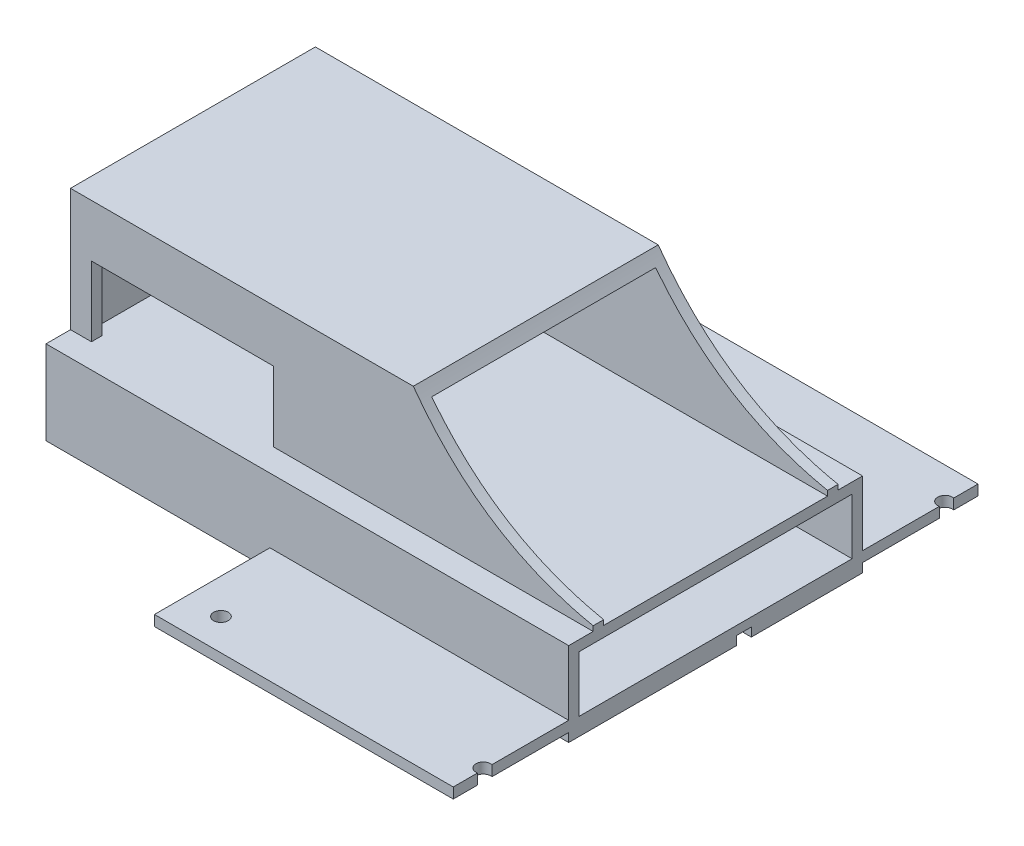
SolidWorks part; units mm, degrees
ref_plane "Plan de face" through (0, 0, 0) normal (0, 0, 1) x (1, 0, 0)
ref_plane "Plan de dessus" through (0, 0, 0) normal (0, 1, 0) x (1, 0, 0)
ref_plane "Plan de droite" through (0, 0, 0) normal (1, 0, 0) x (0, 0, -1)
sketch "Esquisse1" plane through (0, 0, 0) normal (0, 1, 0) x (1, 0, 0)
  line L0 (-54.2982, 57.973) -> (101.7018, 57.973)
  line L1 (-54.2982, 57.973) -> (-54.2982, -26.027)
  line L2 (101.7018, 57.973) -> (101.7018, -26.027)
  line L3 (-54.2982, -26.027) -> (101.7018, -26.027)
  dimension "D1" = 156
  dimension "D2" = 84
extrude "Boss.-Extru.1" add sketch "Esquisse1" along normal blind 59
sketch "Esquisse2" plane through (101.7018, 0, 0) normal (1, 0, 0) x (0, 0, -1)
  line L0 (57.973, 0) -> (57.973, 5)
  line L1 (57.973, 59) -> (57.973, 0) construction
  line L2 (57.973, 5) -> (-26.027, 5)
  line L3 (-26.027, 59) -> (-26.027, 0) construction
  line L4 (-26.027, 5) -> (-26.027, 0)
  line L6 (15.973, 0) -> (21.973, 0)
  line L7 (21.973, 0) -> (21.973, 2.5)
  line L8 (21.973, 2.5) -> (26.173, 2.5)
  line L9 (26.173, 2.5) -> (26.173, 0)
  line L11 (-26.027, 5) -> (-23.027, 5)
  line L12 (-23.027, 5) -> (-23.027, 21)
  line L13 (-23.027, 21) -> (54.973, 21)
  line L14 (54.973, 21) -> (54.973, 5)
  line L15 (54.973, 21) -> (54.973, 24)
  line L16 (54.973, 24) -> (-26.027, 24)
  line L17 (-26.027, 24) -> (57.973, 24)
  line L18 (15.973, 24) -> (47.973, 24)
  line L19 (47.973, 24) -> (47.973, 56)
  line L20 (47.973, 56) -> (-16.027, 56)
  line L21 (-16.027, 56) -> (-16.027, 24)
  line L22 (-16.027, 24) -> (47.973, 24)
  line L23 (47.973, 24) -> (50.973, 24)
  line L24 (50.973, 24) -> (50.973, 59)
  line L25 (-26.027, 59) -> (57.973, 59) construction
  line L26 (-16.027, 24) -> (-19.027, 24)
  line L27 (-19.027, 24) -> (-19.027, 59)
  line L28 (-19.027, 59) -> (50.973, 59)
  line L29 (57.973, 59) -> (57.973, 24)
  line L30 (50.973, 59) -> (57.973, 59)
  line L31 (-19.027, 59) -> (-26.027, 59)
  line L32 (-26.027, 59) -> (-26.027, 24)
  line L33 (21.973, 0) -> (26.173, 0)
  line M8 (-26.027, 0) -> (57.973, 0)
  line M9 (57.973, 0) -> (57.973, 59)
  line M10 (57.973, 59) -> (-26.027, 59)
  line M11 (-26.027, 59) -> (-26.027, 0)
  dimension "D1" = 84
extrude "Enlèv. mat.-Extru.1" cut sketch "Esquisse2" against normal through all contours L20 L21 L16 L17 L19 | L14 L13 L12 L2 | L16 L27 M10 M11 | L24 L16 L17 M9 M10 | L9 L8 L7 M8
sketch "Esquisse3" plane through (0, 0, 19.027) normal (0, 0, 1) x (1, 0, 0)
  line L0 (-54.2982, 59) -> (40.7018, 59)
  line L1 (-54.2982, 59) -> (101.7018, 59) construction
  line L2 (40.7018, 59) -> (40.7018, 24)
  line L3 (-54.2982, 24) -> (101.7018, 24) construction
  line L4 (40.7018, 24) -> (-54.2982, 24)
  line L5 (-54.2982, 24) -> (-54.2982, 59) construction
  line L6 (-54.2982, 24) -> (-54.2982, 59)
  line L7 (40.7018, 59) -> (101.7018, 59)
  line L8 (101.7018, 59) -> (101.7018, 24)
  line L9 (101.7018, 24) -> (40.7018, 24)
  spline S0 degree 2 poles (40.7018, 59) (63.2327, 27.7967) (101.7018, 24) knots 0 0 0 1 1 1
  line M1 (101.7018, 24) -> (101.7018, 59)
  line M2 (101.7018, 59) -> (-54.2982, 59)
extrude "Enlèv. mat.-Extru.3" cut sketch "Esquisse3" against normal through all contours S0 M2 M1
sketch "Esquisse4" plane through (0, 0, 19.027) normal (0, 0, 1) x (1, 0, 0)
  line L0 (-54.2982, 24) -> (-51.2982, 24)
  line L1 (-54.2982, 24) -> (101.7018, 24) construction
  line L2 (-51.2982, 24) -> (-51.2982, 44)
  line L3 (-51.2982, 44) -> (0.7018, 44)
  line L4 (0.7018, 44) -> (0.7018, 24)
  line L5 (0.7018, 24) -> (-51.2982, 24)
  line M1 (-54.2982, 24) -> (101.7018, 24)
extrude "Enlèv. mat.-Extru.4" cut sketch "Esquisse4" against normal blind 59 contours L4 L3 L2 M1
sketch "Esquisse5" plane through (0, 0, -57.973) normal (0, 0, -1) x (-1, 0, 0)
  line L0 (54.2982, 0) -> (54.2982, 2.5)
  line L1 (54.2982, 24) -> (54.2982, 0) construction
  line L2 (54.2982, 2.5) -> (54.2982, 5.5)
  line L3 (54.2982, 0) -> (-40.7018, 0)
  line L4 (-101.7018, 0) -> (54.2982, 0) construction
  line L5 (-40.7018, 0) -> (-40.7018, 5.5)
  line L7 (54.2982, 2.5) -> (-40.7018, 2.75)
  line L9 (-101.7018, 24) -> (-101.7018, 0) construction
  line L10 (-101.7018, 5.5) -> (-101.7018, 2.5)
  line L11 (-101.7018, 2.5) -> (-40.7018, 2.75)
  line L12 (-101.7018, 5.5) -> (-6.7018, 5.5)
  line L13 (-6.7018, 5.5) -> (-6.7018, 2.6605)
  line M7 (-101.7018, 24) -> (-101.7018, 0)
extrude "Boss.-Extru.2" add sketch "Esquisse5" along normal blind 34 contours L12 L11 L5 M7 | L13 L12 L5 L7
sketch "Esquisse6" plane through (0, 0, 26.027) normal (0, 0, 1) x (1, 0, 0)
  line L0 (-54.2982, 0) -> (-54.2982, 2.5)
  line L1 (-54.2982, 24) -> (-54.2982, 0) construction
  line L2 (-54.2982, 2.5) -> (-54.2982, 5.5)
  line L6 (101.7018, 0) -> (101.7018, 2.5)
  line L7 (101.7018, 24) -> (101.7018, 0) construction
  line L8 (101.7018, 2.5) -> (101.7018, 5.5)
  line L9 (101.7018, 5.5) -> (6.7018, 5.5)
  line L10 (6.7018, 5.5) -> (6.7018, 2.5)
  line L11 (6.7018, 2.5) -> (101.7018, 2.5)
extrude "Boss.-Extru.3" add sketch "Esquisse6" along normal blind 34 contours L8 L9 L10 L11
sketch "Esquisse8" plane through (0, 5.5, 0) normal (0, 1, 0) x (1, 0, 0)
  line L0 (101.7018, -60.027) -> (91.7018, -60.027)
  line L1 (101.7018, -60.027) -> (6.7018, -60.027) construction
  line L2 (91.7018, -60.027) -> (91.7018, -50.027)
  line L3 (101.7018, 91.973) -> (91.7018, 91.973)
  line L4 (101.7018, 91.973) -> (6.7018, 91.973) construction
  line L5 (91.7018, 91.973) -> (91.7018, 81.973)
  line L6 (6.7018, 91.973) -> (16.7018, 91.973)
  line L7 (16.7018, 91.973) -> (16.7018, 81.973)
  line L8 (6.7018, -60.027) -> (16.7018, -60.027)
  line L9 (16.7018, -60.027) -> (16.7018, -50.027)
  circle A0 centre (16.7018, -50.027) radius 2.1
  circle A1 centre (91.7018, -50.027) radius 2.1
  circle A2 centre (16.7018, 81.973) radius 2.1
  circle A3 centre (91.7018, 81.973) radius 2.1
extrude "Enlèv. mat.-Extru.5" cut sketch "Esquisse8" against normal blind 37 contours A0 | A1 | A2 | A3
sketch "Esquisse9" plane through (-54.2982, 0, 0) normal (-1, 0, 0) x (0, 0, 1)
  line L0 (-57.973, 0) -> (-57.973, 24)
  line L1 (-57.973, 24) -> (-57.973, 0) construction
  line L2 (-57.973, 24) -> (-50.973, 24)
  line L3 (-50.973, 24) -> (-50.973, 59)
  line L4 (-50.973, 59) -> (19.027, 59)
  line L5 (19.027, 59) -> (19.027, 24)
  line L6 (19.027, 24) -> (26.027, 24)
  line L7 (26.027, 24) -> (26.027, 0)
  line L8 (26.027, 0) -> (-21.973, 0)
  line L9 (-21.973, 0) -> (-21.973, 2.5)
  line L10 (-21.973, 2.5) -> (-26.173, 2.5)
  line L11 (-26.173, 2.5) -> (-26.173, 0) construction
  line L12 (-21.973, 2.5) -> (-26.173, 2.5) construction
  line L13 (-26.173, 2.5) -> (-26.173, 0)
  line L14 (-26.173, 0) -> (-57.973, 0)
extrude "Boss.-Extru.4" add sketch "Esquisse9" along normal blind 3
sketch "Esquisse10" plane through (0, 5.5, 0) normal (0, 1, 0) x (1, 0, 0)
  line L0 (101.7018, 91.973) -> (92.1175, 91.973)
  line L1 (101.7018, 91.973) -> (6.7018, 91.973) construction
  line L2 (92.1175, 91.973) -> (92.1175, -60.027)
  line L3 (101.7018, -60.027) -> (6.7018, -60.027) construction
  line L4 (92.1175, -60.027) -> (101.7018, -60.027)
  line L5 (101.7018, -60.027) -> (101.7018, 91.973)
extrude "Enlèv. mat.-Extru.6" cut sketch "Esquisse10" against normal blind 10 and the other way blind 30
sketch "Esquisse11" plane through (0, 5.5, 0) normal (0, 1, 0) x (1, 0, 0)
  line L0 (6.7018, 91.973) -> (6.7018, 90.973)
  line L1 (6.7018, 91.973) -> (6.7018, 57.973) construction
  line L2 (6.7018, 90.973) -> (92.1175, 90.973)
  line L3 (92.1175, 84.0314) -> (92.1175, 91.973) construction
  line L4 (92.1175, 90.973) -> (92.1175, 91.973)
  line L5 (92.1175, 91.973) -> (6.7018, 91.973)
  line L6 (6.7018, -60.027) -> (6.7018, -59.027)
  line L7 (6.7018, -60.027) -> (6.7018, -26.027) construction
  line L8 (6.7018, -59.027) -> (92.1175, -59.027)
  line L9 (92.1175, -52.0855) -> (92.1175, -60.027) construction
  line L10 (92.1175, -59.027) -> (92.1175, -60.027)
  line L11 (92.1175, -60.027) -> (6.7018, -60.027)
extrude "Enlèv. mat.-Extru.7" cut sketch "Esquisse11" against normal blind 10
